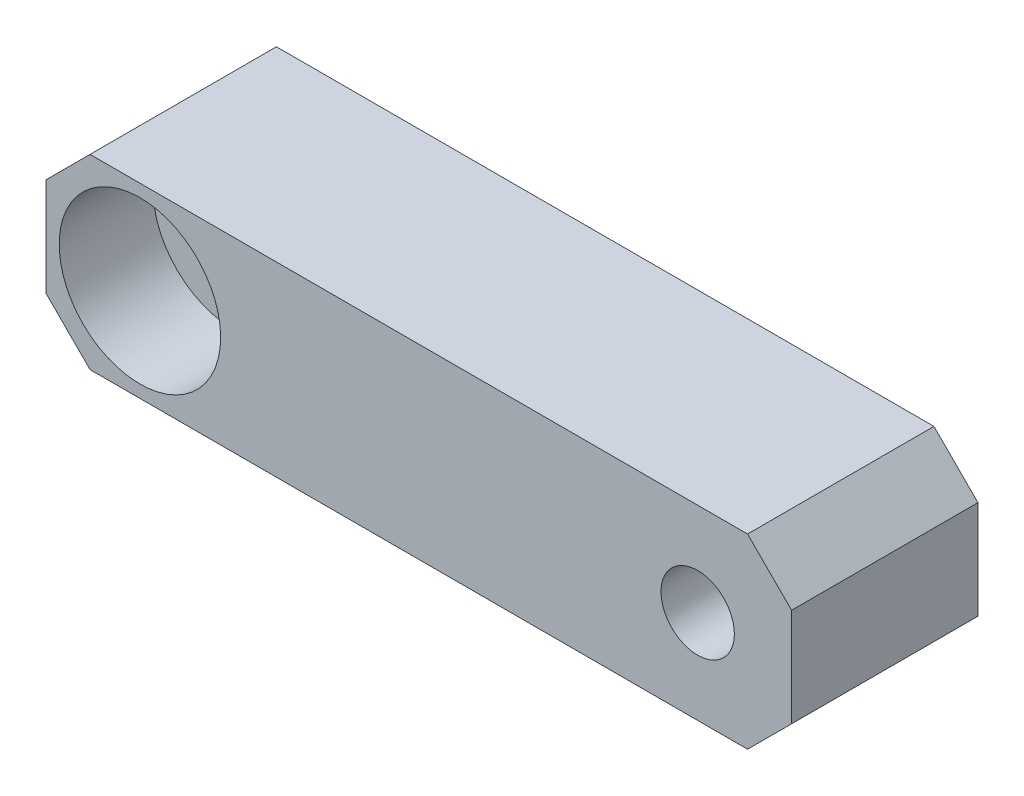
SolidWorks part; units mm, degrees
ref_plane "Alzado" through (0, 0, 0) normal (0, 0, 1) x (1, 0, 0)
ref_plane "Planta" through (0, 0, 0) normal (0, 1, 0) x (1, 0, 0)
ref_plane "Vista lateral" through (0, 0, 0) normal (1, 0, 0) x (0, 0, -1)
sketch "Croquis1" plane through (0, 0, 0) normal (0, 0, 1) x (1, 0, 0)
  line L0 (-22.4, 6.35) -> (-25.4, 3.35)
  line L1 (22.4, 6.35) -> (-22.4, 6.35)
  line L2 (25.4, 3.35) -> (25.4, -3.35)
  line L3 (22.4, -6.35) -> (-22.4, -6.35)
  line L4 (-25.4, 3.35) -> (-25.4, -3.35)
  line L5 (25.4, 6.35) -> (-25.4, -6.35) construction
  line L6 (25.4, -6.35) -> (-25.4, 6.35) construction
  line L7 (-22.4, -6.35) -> (-25.4, -3.35)
  line L8 (25.4, -3.35) -> (22.4, -6.35)
  line L9 (25.4, 3.35) -> (22.4, 6.35)
  point P0 (0, 0)
  dimension "D1" = 12.7
  dimension "D2" = 50.8
extrude "Saliente-Extruir1" add sketch "Croquis1" along normal mid plane 12.7
hole_wizard "Refrentado para tornillo con cabeza hueca de M61" positions "Croquis2" profile "Croquis3" counterbore size "M6" standard "DIN"
sketch "Croquis2" plane through (0, 0, 6.35) normal (0, 0, 1) x (1, 0, 0)
  line L0 (0, 0) -> (0, -50000) construction
  point P0 (19, 0)
  point P8 (-19, 0)
  dimension "D1" = 19
sketch "Croquis3" plane through (19, 0, 6.35) normal (1, 0, 0) x (0, -1, 0)
  line L0 (0, 0) -> (0, 12.7)
  line L1 (0, 12.7) -> (3.3, 12.7)
  line L3 (3.3, 12.7) -> (3.3, 6.4)
  line L4 (3.3, 6.4) -> (5.5, 6.4)
  line L5 (5.5, 6.4) -> (5.5, 0)
  line L7 (5.5, 0) -> (0, 0)
  line L11 (0, -6.35) -> (0, 107.95) construction
  dimension "Diámetro de taladro hasta el siguiente" = 6.6
  dimension "Profundidad de taladro hasta el siguiente" = 12.7
  dimension "Diámetro de refrentado" = 11
  dimension "Profundidad de refrentado" = 6.4
hole_wizard "Taladro roscado M61" positions "Croquis4" profile "Croquis5" tap size "M6" standard "DIN" end condition through all
sketch "Croquis4" plane through (0, 0, 6.35) normal (0, 0, 1) x (1, 0, 0)
  line L0 (0, 0) -> (0, 50000) construction
  point P0 (19, 0)
  point P9 (19, 3.1123)
  point P10 (0, 0)
  dimension "D1" = 19
sketch "Croquis5" plane through (19, 0, 6.35) normal (1, 0, 0) x (0, -1, 0)
  line L0 (0, 0) -> (0, 12.7)
  line L1 (0, 12.7) -> (2.5, 12.7)
  line L2 (2.5, 12.7) -> (2.5, 0)
  line L5 (2.5, 0) -> (0, 0)
  line L11 (0, -6.35) -> (0, 107.95) construction
  dimension "Diámetro de perforador para roscar hasta el siguiente" = 5
  dimension "Profundidad de perforador para roscar hasta el siguiente" = 12.7
cosmetic thread "Rosca de taladro1"
hole_wizard "Refrentado para tornillo con cabeza hueca de M62" positions "Croquis6" profile "Croquis7" counterbore size "M6" standard "DIN" end condition through all
sketch "Croquis6" plane through (0, 0, 6.35) normal (0, 0, 1) x (1, 0, 0)
  point P0 (-19, 0)
  point P2 (0, 0)
  dimension "D1" = 19
sketch "Croquis7" plane through (-19, 0, 6.35) normal (1, 0, 0) x (0, -1, 0)
  line L0 (0, 0) -> (0, 12.7)
  line L1 (0, 12.7) -> (3.3, 12.7)
  line L3 (3.3, 12.7) -> (3.3, 6.4)
  line L4 (3.3, 6.4) -> (5.5, 6.4)
  line L5 (5.5, 6.4) -> (5.5, 0)
  line L7 (5.5, 0) -> (0, 0)
  line L11 (0, -6.35) -> (0, 107.95) construction
  dimension "Diámetro de taladro hasta el siguiente" = 6.6
  dimension "Profundidad de taladro hasta el siguiente" = 12.7
  dimension "Diámetro de refrentado" = 11
  dimension "Profundidad de refrentado" = 6.4
